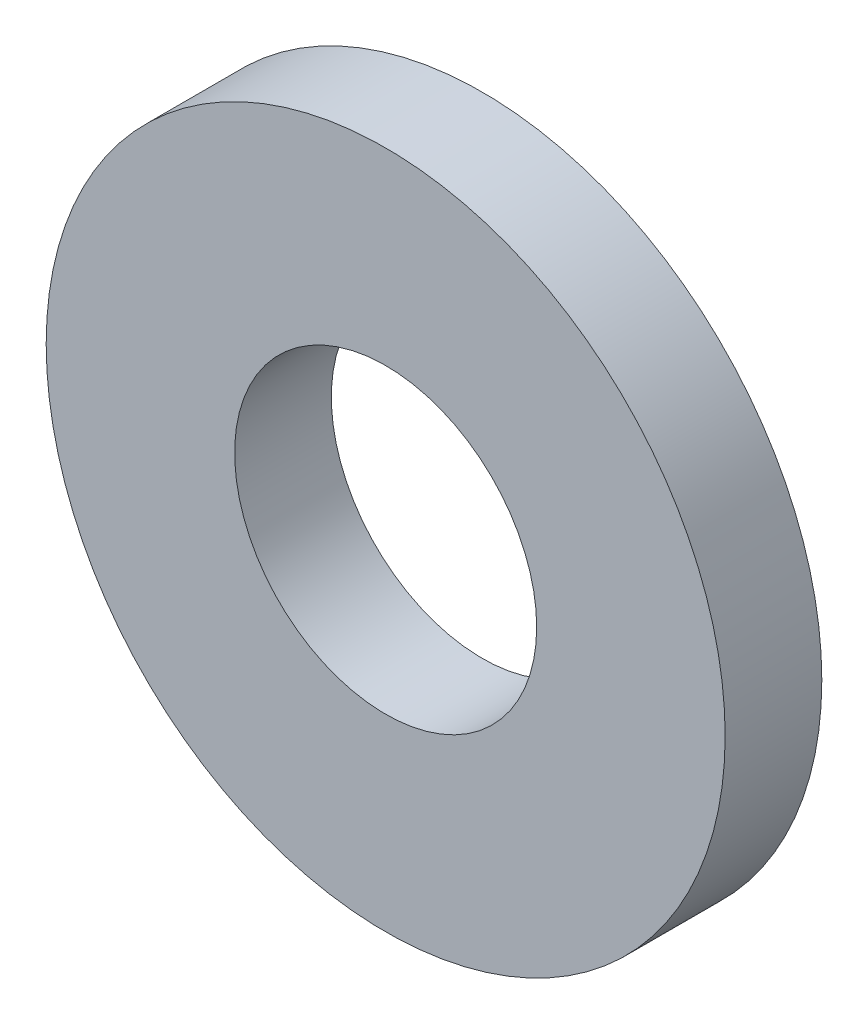
SolidWorks part; units mm, degrees
material "Chrome Stainless Steel"
ref_plane "Front Plane" through (0, 0, 0) normal (0, 0, 1) x (1, 0, 0)
ref_plane "Top Plane" through (0, 0, 0) normal (0, 1, 0) x (1, 0, 0)
ref_plane "Right Plane" through (0, 0, 0) normal (1, 0, 0) x (0, 0, -1)
sketch "Sketch1" plane through (0, 0, 0) normal (0, 1, 0) x (1, 0, 0)
  line L0 (7.1374, 2.032) -> (3.175, 2.032)
  line L1 (3.175, 2.032) -> (3.175, 0)
  line L2 (3.175, 0) -> (7.1374, 0)
  line L3 (7.1374, 0) -> (7.1374, 2.032)
  line L4 (0, 2.032) -> (0, 0) construction
revolve "Revolve1" add sketch "Sketch1" angle 360 about L4
